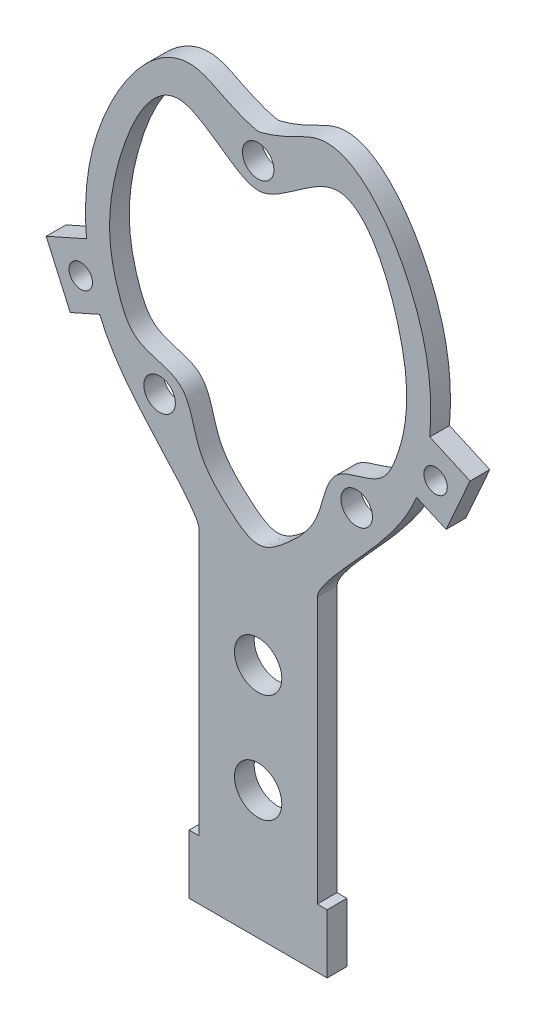
SolidWorks part; units mm, degrees
ref_plane "Front Plane" through (0, 0, 0) normal (0, 0, 1) x (1, 0, 0)
ref_plane "Top Plane" through (0, 0, 0) normal (0, 1, 0) x (1, 0, 0)
ref_plane "Right Plane" through (0, 0, 0) normal (1, 0, 0) x (0, 0, -1)
sketch "Sketch2" plane through (0, 0, 0) normal (0, 0, 1) x (1, 0, 0)
  line L0 (0, -0.0188) -> (0, -6.781) construction
  line L1 (-1.25, 4.75) -> (1.25, 4.75) construction
  line L2 (-4, 6.25) -> (4, 6.25) construction
  line L3 (-7.2, 1.5) -> (7.2, 1.5) construction
  line L4 (-6.25, -5.25) -> (6.25, -5.25) construction
  line L5 (-4, -6.25) -> (4, -6.25) construction
  line L6 (-3, -8.55) -> (3, -8.55) construction
  line L7 (-1.4, -10.55) -> (1.4, -10.55) construction
  line L8 (-5, -7.2) -> (-6.1491, -8.1642) construction
  line L9 (-7, -4) -> (7, -4) construction
  line L10 (0, 1.0146) -> (0, -5.7476) construction
  line L11 (-1, 7.15) -> (1, 7.15) construction
  line L12 (-3.1, 8.05) -> (3.1, 8.05) construction
  line L13 (-8.4144, 1.7962) -> (8.4144, 1.7962) construction
  line L14 (-6.1491, -8.1642) -> (6.1491, -8.1642) construction
  line L16 (-0.5007, -40.6671) -> (-6.3266, 25.9227) construction
  line L17 (-3, -12.1) -> (3, -12.1) construction
  line L18 (-8.6856, -2.4538) -> (8.6856, -2.4538) construction
  line L19 (6.2221, 24.7292) -> (0.3963, -41.8606) construction
  line L20 (-28.4032, 6.85) -> (28.4032, 6.85) construction
  line L21 (-7.2, 1.5) -> (-8.4144, 1.7962) construction
  line L22 (-8.6856, -2.4538) -> (-7.4495, -2.2683) construction
  line L23 (-3, -25.6) -> (-3.5, -25.6)
  line L24 (-3, -12.1) -> (3, -12.1) construction
  line L25 (-3, -12.1) -> (-3, -25.6)
  line L26 (-3, -25.6) -> (3, -25.6) construction
  line L27 (3, -12.1) -> (3, -25.6)
  line L28 (-3, -12.1) -> (3, -25.6) construction
  line L29 (-3, -25.6) -> (3, -12.1) construction
  line L30 (-3.5, -25.6) -> (3.5, -25.6) construction
  line L31 (-3.5, -25.6) -> (-3.5, -28.6)
  line L32 (-3.5, -28.6) -> (3.5, -28.6)
  line L33 (3.5, -25.6) -> (3.5, -28.6)
  line L34 (-3.5, -25.6) -> (3.5, -28.6) construction
  line L35 (-3.5, -28.6) -> (3.5, -25.6) construction
  line L36 (3.5, -25.6) -> (3, -25.6)
  circle A2 centre (0, -16.6) radius 1.2
  circle A3 centre (0, 5.55) radius 0.8
  circle A4 centre (-5, -7.2) radius 0.8
  circle A5 centre (5, -7.2) radius 0.8
  circle A6 centre (0, -22.1) radius 1.2
  spline S0 degree 3 poles (1.8069, 5.0163) (0, 4.0197) (-1.8069, 5.0163) (-4.9012, 7.7541) (-7.771, 1.1281) (-7.6313, -2.6614) (-6.2568, -5.758) (-3.5015, -5.7609) (-3.2301, -8.7844) (-1.7453, -10.314) (0, -11.6774) (1.7453, -10.314) (3.2301, -8.7844) (3.5015, -5.7609) (6.2568, -5.758) (7.6313, -2.6614) (7.771, 1.1281) (4.9012, 7.7541) (1.8069, 5.0163) (0, 4.0197) (-1.8069, 5.0163) knots -0.194127 -0.085189 -0.025607 0 0.025607 0.085189 0.194127 0.29881 0.326537 0.37337 0.421074 0.469791 0.5 0.530209 0.578926 0.62663 0.673463 0.70119 0.805873 0.914811 0.974393 1 1.025607 1.085189 1.194127 only from (0, 4.25) to (0, 4.25)
  spline S1 degree 3 poles (3, -12.1) (3.0581, -11.4359) (7.3722, -7.2617) (8.8163, -3.8196) (8.7952, 3.0882) (4.7299, 9.5027) (1.5431, 7.2852) (0.1384, 6.8487) (-0.1384, 6.8487) (-1.5431, 7.2852) (-4.7299, 9.5027) (-8.7952, 3.0882) (-8.8163, -3.8196) (-7.3722, -7.2617) (-3.0581, -11.4359) (-3, -12.1) knots 0.110532 0.110532 0.110532 0.110532 0.195871 0.310872 0.37508 0.502014 0.537662 0.553506 0.557026 0.57287 0.608518 0.735452 0.79966 0.914661 1 1 1 1
  point P5 (0, 0)
  point P9 (0, -6.25)
  point P40 (0, -2.2618)
  point P45 (0, -27.1)
  point P51 (0, 4.75)
  point P58 (0, 6.25)
  point P60 (0, 1.5)
  point P62 (0, -4)
  point P64 (0, -5.25)
  point P68 (0, -8.55)
  point P86 (0, -12.1)
  point P89 (0, 7.15)
  point P90 (0, 8.05)
  point P91 (0, 1.7962)
  point P92 (0, -2.4538)
  point P93 (0, -8.1642)
  point P100 (0, -10.55)
  point P101 (0, -25.6)
  point P102 (0, -18.85)
  dimension "D32" = 1
  dimension "D36" = 2
  dimension "D37" = 2
  dimension "D40" = 1.6
  dimension "D6" = 0.5
  dimension "D46" = 2.4
  dimension "D1" = 6
  dimension "D2" = 13.5
  dimension "D3" = 1.5
  dimension "D5" = 7.2
  dimension "D7" = 2.6
  dimension "D8" = 4.25
  dimension "D9" = 1.25
  dimension "D10" = 2
  dimension "D11" = 4
  dimension "D12" = 0.3
  dimension "D13" = 0.9
  dimension "D14" = 3.1
  dimension "D15" = 4
  dimension "D16" = 7
  dimension "D17" = 1.25
  dimension "D18" = 5.25
  dimension "D19" = 6.25
  dimension "D20" = 6.25
  dimension "D21" = 4
  dimension "D22" = 8.55
  dimension "D23" = 3
  dimension "D24" = 1.5
  dimension "D25" = 40
  dimension "D27" = 10.55
  dimension "D28" = 1.4
  dimension "D29" = 11.3
  dimension "D31" = 0.8
  dimension "D33" = 90
  dimension "D34" = 1
  dimension "D35" = 1.25
  dimension "D38" = 175
  dimension "D39" = 175
  dimension "D41" = 1.3
  dimension "D42" = 12.75
  dimension "D43" = 5
  dimension "D44" = 3
  dimension "D45" = 7
  dimension "D47" = 3.5
  dimension "D48" = 5.5
extrude "Boss-Extrude2" add sketch "Sketch2" along normal blind 1 separate body
sketch "Sketch3" plane through (0, 0, 0) normal (0, 0, 1) x (1, 0, 0)
  line L0 (-7.4013, -3.2882) -> (-10.1419, -4.5084) construction
  line L5 (-8.0114, -1.9179) -> (-6.7912, -4.6585)
  line L6 (-8.0114, -1.9179) -> (-10.752, -3.1381)
  line L8 (-10.752, -3.1381) -> (-9.5318, -5.8787)
  line L9 (-6.7912, -4.6585) -> (-9.5318, -5.8787)
  line L10 (0, 0) -> (0, -5.2835) construction
  line L11 (-8.0114, -1.9179) -> (-10.752, -3.1381)
  line L12 (-6.7912, -4.6585) -> (-9.5318, -5.8787)
  line L13 (7.4013, -3.2882) -> (10.1419, -4.5084) construction
  line L14 (6.7912, -4.6585) -> (9.5318, -5.8787)
  line L15 (8.0114, -1.9179) -> (10.752, -3.1381)
  line L16 (6.7912, -4.6585) -> (9.5318, -5.8787)
  line L17 (10.752, -3.1381) -> (9.5318, -5.8787)
  line L18 (8.0114, -1.9179) -> (10.752, -3.1381)
  line L19 (8.0114, -1.9179) -> (6.7912, -4.6585)
  point P5 (-9, -4)
  point P25 (9, -4)
  dimension "D1" = 3
  dimension "D2" = 24
  dimension "D3" = 1.25
  dimension "D4" = 9
  dimension "D5" = 4
extrude "Boss-Extrude3" add sketch "Sketch3" along normal blind 1 contours L9 L5 L6 L8 | L15 L19 L14 L17
sketch "Sketch4" plane through (0, 0, 0) normal (0, 0, 1) x (1, 0, 0)
  line L0 (-10.1419, -4.5084) -> (-9, -4) construction
  line L3 (-10.752, -3.1381) -> (-9.5318, -5.8787) construction
  line L6 (-8.7065, -2.2274) -> (-10.752, -3.1381) construction
  line L7 (0, 0) -> (0, -3.1391) construction
  circle A0 centre (-9, -4) radius 0.595
  circle A2 centre (9, -4) radius 0.595
  dimension "D1" = 1.19
  dimension "D2" = 1.25
extrude "Cut-Extrude10" cut sketch "Sketch4" along normal blind 10
